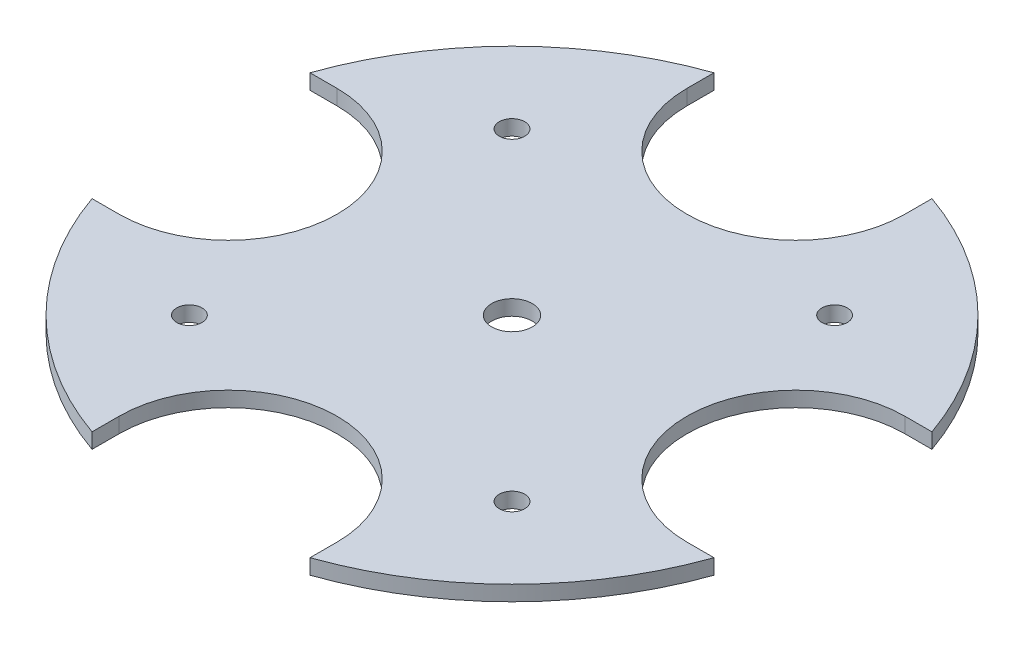
SolidWorks part; units mm, degrees
ref_plane "Front Plane" through (0, 0, 0) normal (0, 0, 1) x (1, 0, 0)
ref_plane "Top Plane" through (0, 0, 0) normal (0, 1, 0) x (1, 0, 0)
ref_plane "Right Plane" through (0, 0, 0) normal (1, 0, 0) x (0, 0, -1)
sketch "Sketch1" plane through (0, 0, 0) normal (0, 1, 0) x (1, 0, 0)
  line L1 (-56, 21.5) -> (-61.3413, 21.5)
  line L2 (-56, -21.5) -> (-61.3413, -21.5)
  line L3 (21.5, 56) -> (21.5, 61.3413)
  line L4 (-21.5, 56) -> (-21.5, 61.3413)
  line L5 (56, -21.5) -> (61.3413, -21.5)
  line L6 (56, 21.5) -> (61.3413, 21.5)
  line L7 (-21.5, -56) -> (-21.5, -61.3413)
  line L8 (21.5, -56) -> (21.5, -61.3413)
  arc A0 (-61.3413, -21.5) -> (-21.5, -61.3413) centre (0, 0) ccw
  arc A1 (-56, -21.5) -> (-56, 21.5) centre (-56, 0) ccw
  arc A2 (-21.5, 56) -> (21.5, 56) centre (0, 56) ccw
  arc A3 (56, 21.5) -> (56, -21.5) centre (56, 0) ccw
  arc A4 (21.5, -56) -> (-21.5, -56) centre (0, -56) ccw
  arc A5 (-21.5, 61.3413) -> (-61.3413, 21.5) centre (0, 0) ccw
  arc A6 (61.3413, 21.5) -> (21.5, 61.3413) centre (0, 0) ccw
  arc A7 (21.5, -61.3413) -> (61.3413, -21.5) centre (0, 0) ccw
  circle A8 centre (0, 0) radius 4
  circle A9 centre (-31.8198, 31.8198) radius 2.5
  circle A10 centre (31.8198, 31.8198) radius 2.5
  circle A11 centre (31.8198, -31.8198) radius 2.5
  circle A12 centre (-31.8198, -31.8198) radius 2.5
  point P26 (0, 0)
  point P37 (0, 0)
  dimension "D1" = 130
  dimension "D3" = 43
  dimension "D5" = 8
  dimension "D6" = 5
  dimension "D7" = 45
  dimension "D4" = 4
  dimension "D8" = 4
extrude "Boss-Extrude1" add sketch "Sketch1" along normal blind 3
